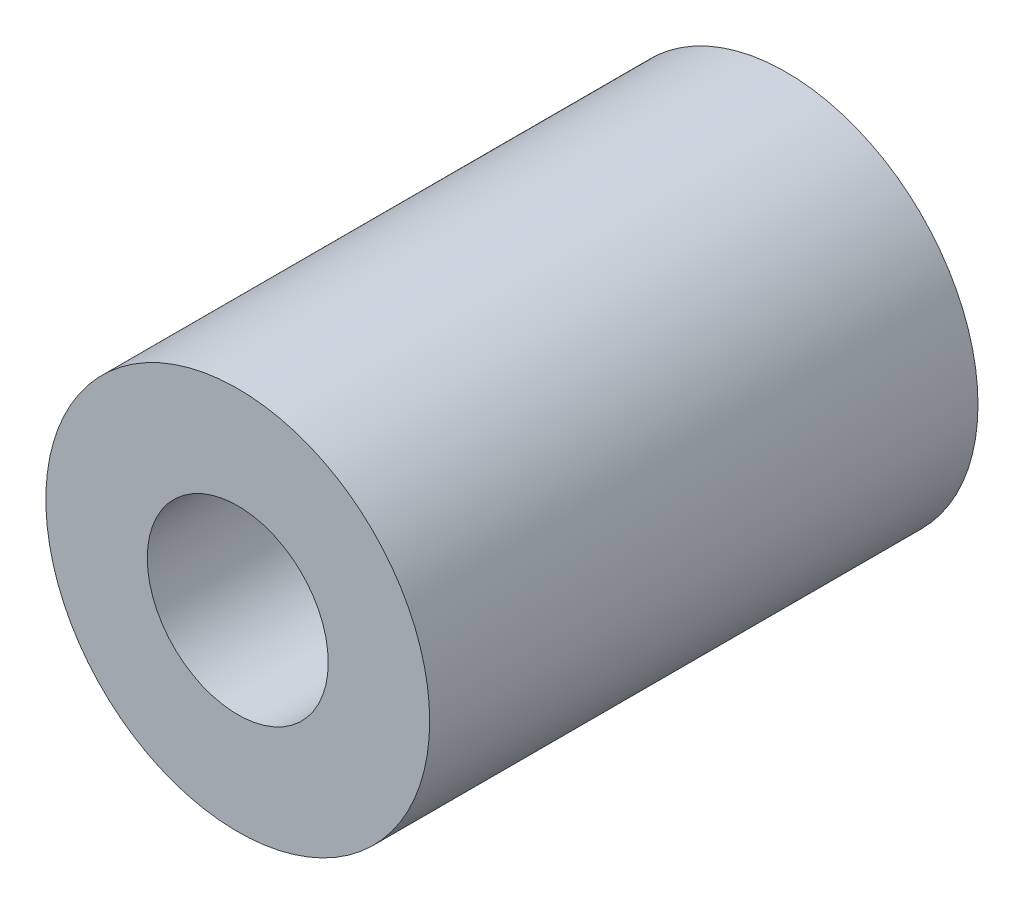
SolidWorks part; units mm, degrees
material "ABS"
ref_plane "前视基准面" through (0, 0, 0) normal (0, 0, 1) x (1, 0, 0)
ref_plane "上视基准面" through (0, 0, 0) normal (0, 1, 0) x (1, 0, 0)
ref_plane "右视基准面" through (0, 0, 0) normal (1, 0, 0) x (0, 0, -1)
other "Configuration Table"
sketch "草图1" plane through (0, 0, 0) normal (0, 0, 1) x (1, 0, 0)
  circle A0 centre (0, 0) radius 1.65
  circle A1 centre (0, 0) radius 3.5
  dimension "D1" = 3.3
  dimension "D2" = 7
extrude "凸台-拉伸1" add sketch "草图1" along normal blind 10
